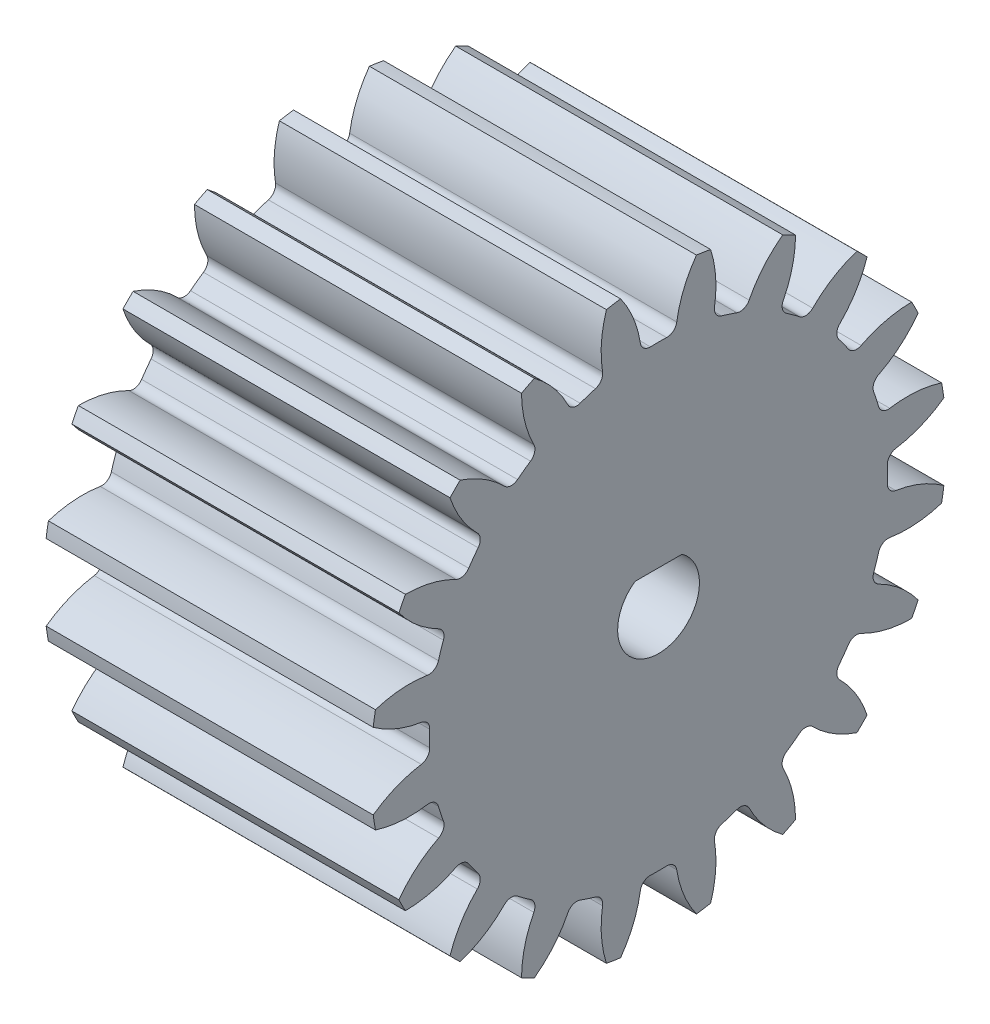
SolidWorks part; units mm, degrees
ref_plane "Front Plane" through (0, 0, 0) normal (0, 0, 1) x (1, 0, 0)
ref_plane "Top Plane" through (0, 0, 0) normal (0, 1, 0) x (1, 0, 0)
ref_plane "Right Plane" through (0, 0, 0) normal (1, 0, 0) x (0, 0, -1)
sketch "Sketch1" plane through (0, 0, 0) normal (1, 0, 0) x (0, 0, -1)
  circle A0 centre (0, 0) radius 3.125
  circle A1 centre (0, 0) radius 22
  dimension "D1" = 6.25
  dimension "D2" = 44
extrude "Boss-Extrude2" add sketch "Sketch1" along normal blind 25
sketch "Sketch3" plane through (25, 0, 0) normal (1, 0, 0) x (0, 0, -1)
  line L0 (0, 0) -> (0, 22) construction
  line L1 (-1.3128, 17.4507) -> (0, 0) construction
  line L2 (0, 14.7782) -> (-1.4216, 18.684) construction
  circle A0 centre (0, 0) radius 22 construction
  arc A1 (1.3128, 17.4507) -> (-1.3128, 17.4507) centre (0, 0) ccw
  arc A2 (1.8708, 19.9123) -> (-1.8708, 19.9123) centre (0, 0) ccw construction
  arc A3 (2.8988, 21.8082) -> (-2.8988, 21.8082) centre (0, 0) ccw
  arc A4 (-2.8988, 21.8082) -> (-1.3128, 17.4507) centre (-9.8582, 16.8078) cw
  arc A5 (2.8988, 21.8082) -> (1.3128, 17.4507) centre (9.8582, 16.8078) ccw
  point P17 (-1.8055, 19.7388)
  dimension "D1" = 44
  dimension "D2" = 40
  dimension "D3" = 4.5
  dimension "D4" = 20
  dimension "D5" = 3.7416
extrude "Cut-Extrude1" cut sketch "Sketch3" against normal through all
fillet "Fillet1" radius 0.76 2 edges at (12.5, 17.4507, -1.3128) (12.5, 17.4507, 1.3128)
pattern_circular "CirPattern2" count 20 over 360 about axis through (0, 0, 0) along (1, 0, 0) of "Fillet1", "Cut-Extrude1"
sketch "Sketch4" plane through (0, 0, 0) normal (-1, 0, 0) x (0, 0, 1)
  line L0 (1.2919, -2.8455) -> (3, -2.8455) construction
  line L5 (-1.8, 2.5545) -> (1.8, 2.5545)
  circle A0 centre (0, 0) radius 3.125 construction
  arc A1 (-1.8, 2.5545) -> (1.8, 2.5545) centre (0, 0.1545) cw
  dimension "D2" = 3
  dimension "D1" = 5.4
  dimension "D3" = 3.6
extrude "Boss-Extrude3" add sketch "Sketch4" against normal up to surface (25 mm away) up to face at (25, 0, -3.125)
equation "\"No of teeth\" = 20"
equation "\"Module\"= 2"
equation "\"Outer Diameter\"= ( \"No of teeth\" + 2 ) * \"Module\""
equation "\"Pitch Diameter\"= \"No of teeth\" * \"Module\""
equation "\"Backlash\"= 0.3 * \"Module\""
equation "\"Arc Length\"= ( ( \"Module\" * pi ) / 2 ) + \"Backlash\""
equation "\"Fillet Radius\"= 0.38 * \"Module\""
equation "\"Bore Diameter\"= 6.25"
equation "\"Presseure angle\"= 20"
equation "\"Tooth Design\"= IIF ( \"Module\" <= 1.25 , 2.4 * \"Module\" , 2.25 * \"Module\" )"
equation "\"D1@Sketch1\"=\"Bore Diameter\""
equation "\"D2@Sketch1\"=\"Outer Diameter\""
equation "\"D1@Sketch3\"=\"Outer Diameter\""
equation "\"D2@Sketch3\"=\"Pitch Diameter\""
equation "\"D3@Sketch3\"=\"Tooth Design\""
equation "\"D4@Sketch3\"=\"Presseure angle\""
equation "\"D5@Sketch3\"=\"Arc Length\""
equation "\"D1@Fillet1\"=\"Fillet Radius\""
equation "\"D1@CirPattern2\"=\"No of teeth\""
